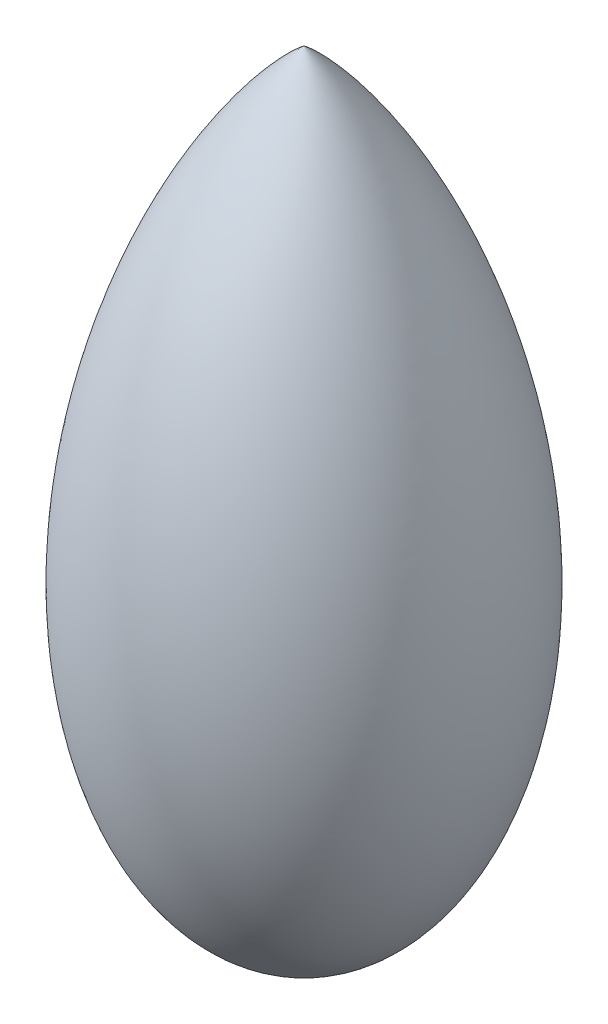
SolidWorks part; units mm, degrees
ref_plane "Front Plane" through (0, 0, 0) normal (0, 0, 1) x (1, 0, 0)
ref_plane "Top Plane" through (0, 0, 0) normal (0, 1, 0) x (1, 0, 0)
ref_plane "Right Plane" through (0, 0, 0) normal (1, 0, 0) x (0, 0, -1)
sketch "Sketch" plane through (0, 0, 0) normal (0, 0, 1) x (1, 0, 0)
  line L0 (0, 0) -> (0, -397.8874) construction
  line L1 (0, 0) -> (0, -397.8874)
  spline S0 degree 4 poles (0, 0) (0.0759, -0.0549) (0.227, -0.1659) (0.5257, -0.3924) (1.1154, -0.8554) (1.9854, -1.5672) (3.1234, -2.5419) (4.4488, -3.7284) (5.8192, -5.0037) (7.505, -6.6264) (9.4886, -8.6141) (11.7337, -10.9647) (14.2225, -13.693) (17.2376, -17.1374) (20.7322, -21.3365) (24.6704, -26.3478) (30.076, -33.6746) (36.2317, -42.7032) (44.8868, -56.6252) (55.2691, -75.8687) (65.7944, -99.1143) (75.7143, -126.5355) (83.5256, -154.6294) (89.1749, -183.2377) (92.1348, -208.5834) (93.1535, -230.4248) (92.9166, -248.6371) (92.0398, -263.1823) (90.6345, -275.8555) (88.9423, -286.6515) (87.1881, -295.586) (85.57, -302.6881) (83.728, -309.7356) (81.6521, -316.7179) (79.3313, -323.6229) (76.7537, -330.4364) (73.8696, -337.2277) (70.6527, -343.9719) (67.1178, -350.5557) (63.2466, -356.948) (59.0792, -363.039) (54.6129, -368.7977) (49.8452, -374.1773) (45.395, -378.5339) (41.4046, -381.9683) (38.1979, -384.4404) (35.8068, -386.1423) (33.5685, -387.6188) (31.4998, -388.89) (29.39, -390.0919) (27.2404, -391.2211) (25.0523, -392.2738) (22.8276, -393.2467) (20.0031, -394.3584) (17.1251, -395.3254) (14.1994, -396.1395) (11.5323, -396.7283) (9.7407, -397.0595) (8.2433, -397.2939) (7.0368, -397.4562) (5.8372, -397.5931) (4.6169, -397.7045) (3.4258, -397.7902) (2.1782, -397.8501) (1.2316, -397.8783) (0.2847, -397.8883) (-0.317, -397.8873) (-0.9547, -397.8812) (-1.5286, -397.8678) (-2.3198, -397.8428) (-3.2315, -397.7993) (-4.3163, -397.7292) (-5.5406, -397.6225) (-6.7696, -397.4893) (-7.9912, -397.3299) (-9.2117, -397.1445) (-10.4264, -396.9333) (-11.6374, -396.6965) (-12.8426, -396.4344) (-14.3423, -396.0757) (-16.1294, -395.5959) (-18.1946, -394.966) (-20.5244, -394.1529) (-22.8208, -393.2501) (-25.0814, -392.2611) (-27.8788, -390.9126) (-31.1699, -389.1263) (-33.8287, -387.4778) (-35.9025, -386.0641) (-36.9242, -385.3358) knots 0 0 0 0 0 0.000743 0.001486 0.002971 0.005943 0.009652 0.013362 0.017071 0.020781 0.028199 0.035618 0.042834 0.050051 0.064483 0.078915 0.093348 0.122213 0.151077 0.208807 0.266536 0.324266 0.381995 0.439725 0.497454 0.526319 0.555184 0.584049 0.612913 0.627346 0.641778 0.656211 0.670643 0.685075 0.699508 0.71394 0.728372 0.743545 0.758717 0.773149 0.787581 0.802014 0.816446 0.830083 0.836902 0.84372 0.848531 0.853342 0.858153 0.862964 0.867774 0.872585 0.877396 0.882207 0.891828 0.896639 0.90145 0.903855 0.906261 0.908666 0.911071 0.913477 0.915882 0.918287 0.920693 0.921447 0.922669 0.923891 0.925113 0.926335 0.92878 0.931224 0.933668 0.936113 0.938557 0.941001 0.943445 0.94589 0.948334 0.950778 0.955667 0.960555 0.965444 0.970333 0.975221 0.98011 0.990055 1 1 1 1 1 construction
  spline S1 degree 4 poles (0, 0) (0.0759, -0.0549) (0.227, -0.1659) (0.5257, -0.3924) (1.1154, -0.8554) (1.9854, -1.5672) (3.1234, -2.5419) (4.4488, -3.7284) (5.8192, -5.0037) (7.505, -6.6264) (9.4886, -8.6141) (11.7337, -10.9647) (14.2225, -13.693) (17.2376, -17.1374) (20.7322, -21.3365) (24.6704, -26.3478) (30.076, -33.6746) (36.2317, -42.7032) (44.8868, -56.6252) (55.2691, -75.8687) (65.7944, -99.1143) (75.7143, -126.5355) (83.5256, -154.6294) (89.1749, -183.2377) (92.1348, -208.5834) (93.1535, -230.4248) (92.9166, -248.6371) (92.0398, -263.1823) (90.6345, -275.8555) (88.9423, -286.6515) (87.1881, -295.586) (85.57, -302.6881) (83.728, -309.7356) (81.6521, -316.7179) (79.3313, -323.6229) (76.7537, -330.4364) (73.8696, -337.2277) (70.6527, -343.9719) (67.1178, -350.5557) (63.2466, -356.948) (59.0792, -363.039) (54.6129, -368.7977) (49.8452, -374.1773) (45.395, -378.5339) (41.4046, -381.9683) (38.1979, -384.4404) (35.8068, -386.1423) (33.5685, -387.6188) (31.4998, -388.89) (29.39, -390.0919) (27.2404, -391.2211) (25.0523, -392.2738) (22.8276, -393.2467) (20.0031, -394.3584) (17.1251, -395.3254) (14.1994, -396.1395) (11.5323, -396.7283) (9.7407, -397.0595) (8.2433, -397.2939) (7.0368, -397.4562) (5.8372, -397.5931) (4.6169, -397.7045) (3.4258, -397.7902) (2.1782, -397.8501) (1.2316, -397.8783) (0.4552, -397.8865) (0.0877, -397.8874) (0, -397.8874) knots 0 0 0 0 0 0.000743 0.001486 0.002971 0.005943 0.009652 0.013362 0.017071 0.020781 0.028199 0.035618 0.042834 0.050051 0.064483 0.078915 0.093348 0.122213 0.151077 0.208807 0.266536 0.324266 0.381995 0.439725 0.497454 0.526319 0.555184 0.584049 0.612913 0.627346 0.641778 0.656211 0.670643 0.685075 0.699508 0.71394 0.728372 0.743545 0.758717 0.773149 0.787581 0.802014 0.816446 0.830083 0.836902 0.84372 0.848531 0.853342 0.858153 0.862964 0.867774 0.872585 0.877396 0.882207 0.891828 0.896639 0.90145 0.903855 0.906261 0.908666 0.911071 0.913477 0.915882 0.918287 0.920693 0.921447 0.921447 0.921447 0.921447 0.921447
revolve "Revolve" add sketch "Sketch" angle 360 about L0
